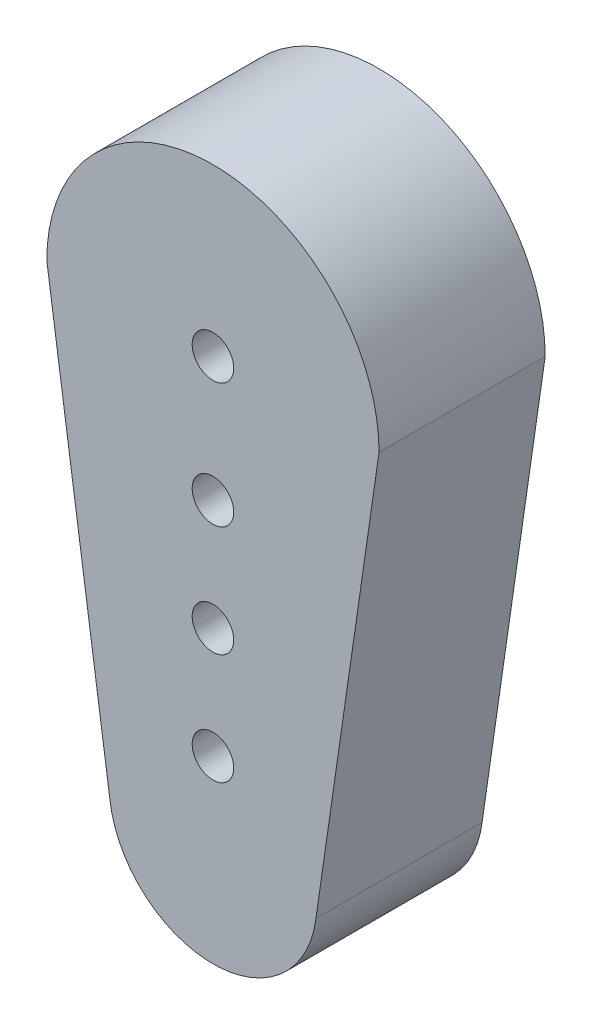
SolidWorks part; units mm, degrees
ref_plane "Front Plane" through (0, 0, 0) normal (0, 0, 1) x (1, 0, 0)
ref_plane "Top Plane" through (0, 0, 0) normal (0, 1, 0) x (1, 0, 0)
ref_plane "Right Plane" through (0, 0, 0) normal (1, 0, 0) x (0, 0, -1)
sketch "Sketch2" plane through (0, 0, 0) normal (0, 0, 1) x (1, 0, 0)
  line L0 (0, -55) -> (0, 55) construction
  line L1 (-6, 0) -> (-3.7206, -15.7189)
  line L2 (6, 0) -> (3.7206, -15.7189)
  arc A0 (6, 0) -> (-6, 0) centre (0, 0) ccw
  arc A1 (-3.7206, -15.7189) -> (3.7206, -15.7189) centre (0, -15.25) ccw
  point P1 (-2.5, -15.5)
  point P3 (-3, -15)
  point P11 (-2.9004, -15.7666)
  point P12 (0, 0)
  point P13 (0, 0)
  point P14 (2.9001, -15.7666)
  point P15 (2.9673, -16.5583)
  point P16 (-2.6467, -18.4123)
  point P17 (2.6143, -18.4123)
  point P18 (-3.7206, -14.7189)
  point P19 (3.7206, -14.7189)
  dimension "D1" = 12
  dimension "D2" = 7.5
  dimension "D3" = 19
extrude "Boss-Extrude1" add sketch "Sketch2" along normal blind 6
sketch "Sketch3" plane through (0, 0, 0) normal (0, 0, 1) x (1, 0, 0)
  line L0 (-3.75, 0) -> (-2.25, -15)
  line L1 (2.25, -15) -> (3.75, 0)
  line L2 (0, -3.3) -> (0, 3.3) construction
  arc A0 (3.75, 0) -> (-3.75, 0) centre (0, 0) ccw
  arc A1 (-2.25, -15) -> (2.25, -15) centre (0, -15) ccw
  dimension "D1" = 7.5
  dimension "D2" = 4.5
  dimension "D3" = 15
extrude "Cut-Extrude3" cut sketch "Sketch3" along normal blind 4.7
sketch "Sketch4" plane through (0, 0, 4.7) normal (0, 0, -1) x (-1, 0, 0)
  circle A0 centre (0, 0) radius 0.75
  dimension "D1" = 1.5
extrude "Cut-Extrude4" cut sketch "Sketch4" against normal through all both and the other way through all
sketch "Sketch6" plane through (0, 0, 4.7) normal (0, 0, -1) x (-1, 0, 0)
  line L0 (0, 55) -> (0, -55) construction
  line L1 (55, 0) -> (-55, 0) construction
  circle A0 centre (0, -4.5) radius 0.75
  dimension "D1" = 1.5
  dimension "D2" = 4.5
extrude "Cut-Extrude6" cut sketch "Sketch6" against normal through all both and the other way through all
pattern_linear "LPattern1" count 3 spacing 4 along (0, -1, 0) of "Cut-Extrude6"
scale "Scale1" scale about centroid uniform scaling yes scale factor 1.02
